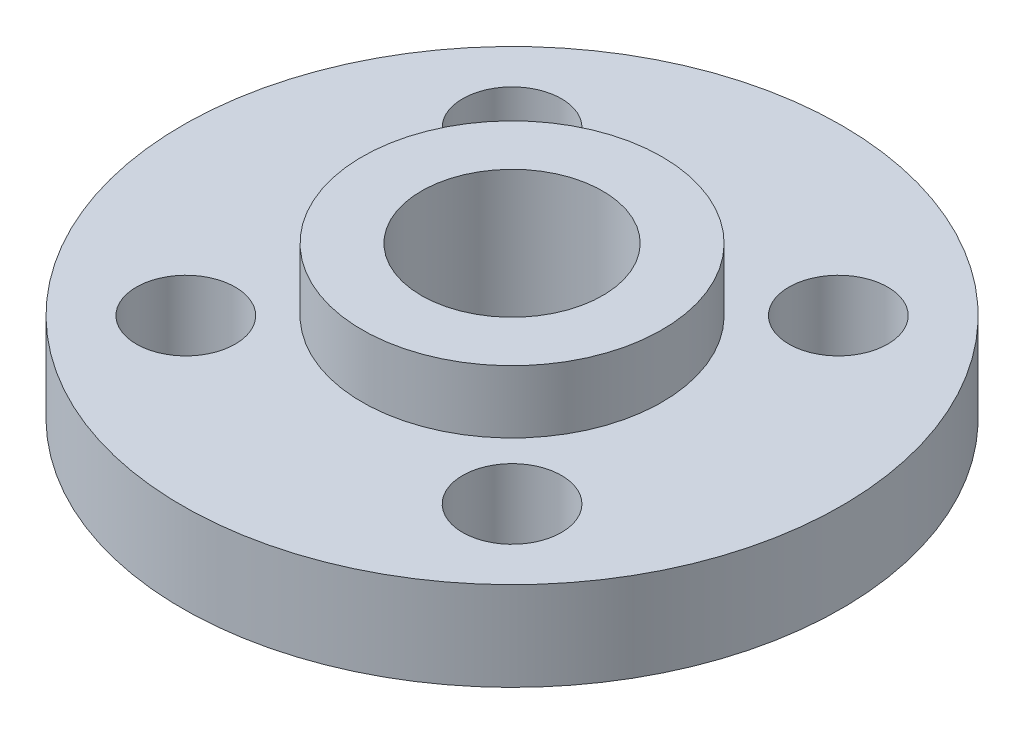
SolidWorks part; units mm, degrees
ref_plane "Plan de face" through (0, 0, 0) normal (0, 0, 1) x (1, 0, 0)
ref_plane "Plan de dessus" through (0, 0, 0) normal (0, 1, 0) x (1, 0, 0)
ref_plane "Plan de droite" through (0, 0, 0) normal (1, 0, 0) x (0, 0, -1)
sketch "Esquisse1" plane through (0, 0, 0) normal (0, 1, 0) x (1, 0, 0)
  circle A0 centre (0, 0) radius 10
  circle A1 centre (0, 0) radius 1.6
  dimension "D1" = 20
  dimension "D2" = 3.2
extrude "Boss.-Extru.1" add sketch "Esquisse1" along normal blind 2.7
sketch "Esquisse2" plane through (0, 2.7, 0) normal (0, 1, 0) x (1, 0, 0)
  circle A1 centre (0, 0) radius 4.55
  dimension "D2" = 9.1
extrude "Boss.-Extru.2" add sketch "Esquisse2" along normal blind 1.9
sketch "Esquisse5" plane through (0, 4.6, 0) normal (0, 1, 0) x (1, 0, 0)
  circle A1 centre (0, 0) radius 2.75
  dimension "D1" = 5.5
extrude "Enlèv. mat.-Extru.1" cut sketch "Esquisse5" against normal blind 4
hole_wizard "Diamètre du perçage Ø3.0 (3)1" positions "Esquisse3" profile "Esquisse4" hole size "Ø3.0" standard "DIN" end condition through all
sketch "Esquisse3" plane through (0, 2.7, 0) normal (0, 1, 0) x (1, 0, 0)
  line L2 (-4.9497, 4.9497) -> (4.9497, 4.9497) construction
  line L3 (-4.9497, 4.9497) -> (-4.9497, -4.9497) construction
  line L4 (-4.9497, -4.9497) -> (4.9497, -4.9497) construction
  line L5 (4.9497, 4.9497) -> (4.9497, -4.9497) construction
  circle A0 centre (0, 0) radius 7 construction
  point P0 (4.9497, -4.9497)
  point P2 (-4.9497, -4.9497)
  point P4 (-4.9497, 4.9497)
  point P6 (4.9497, 4.9497)
  dimension "D1" = 14
sketch "Esquisse4" plane through (4.9497, 2.7, 4.9497) normal (1, 0, 0) x (0, 0, 1)
  line L0 (0, 0) -> (0, 2.7)
  line L1 (0, 2.7) -> (1.5, 2.7)
  line L2 (1.5, 2.7) -> (1.5, 0)
  line L5 (1.5, 0) -> (0, 0)
  line L11 (0, -6.35) -> (0, 107.95) construction
  dimension "Diamètre du perçage jusqu'au prochain" = 3
  dimension "Profondeur du perçage jusqu'au prochain" = 2.7
